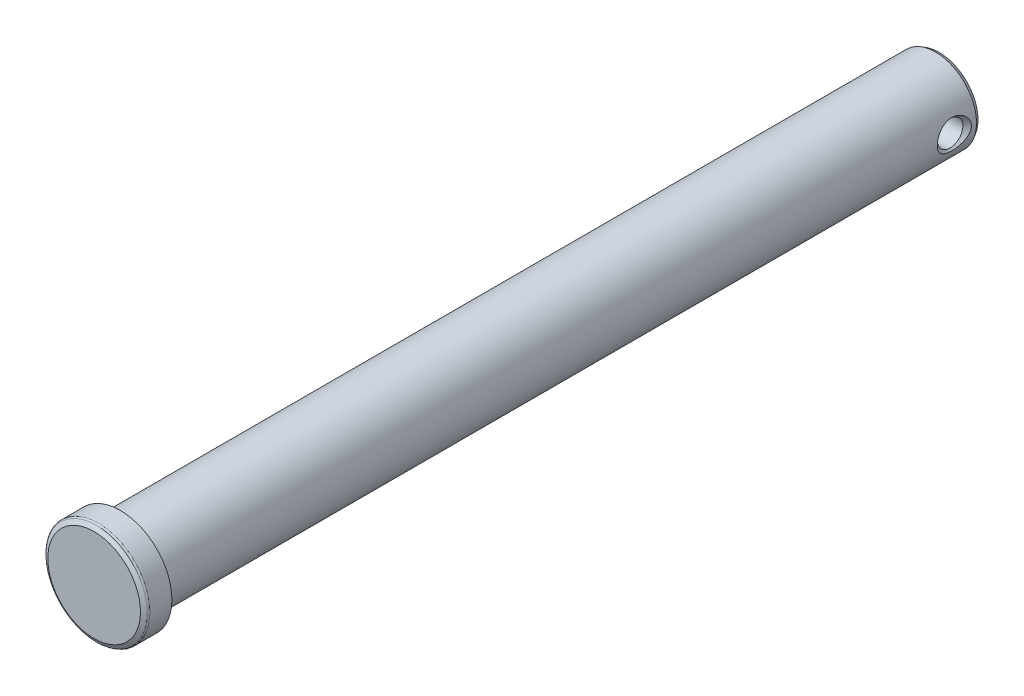
SolidWorks part; units mm, degrees
ref_plane "Front" through (0, 0, 0) normal (0, 0, 1) x (1, 0, 0)
ref_plane "Top" through (0, 0, 0) normal (0, 1, 0) x (1, 0, 0)
ref_plane "Right" through (0, 0, 0) normal (1, 0, 0) x (0, 0, -1)
sketch "Sketch1" plane through (0, 0, 0) normal (1, 0, 0) x (0, 0, -1)
  line L0 (-67.564, 0) -> (-63.5, 0) construction
  line L1 (-63.5, 0) -> (63.5, 0) construction
  line L2 (-67.564, 0) -> (-67.564, 7.1882)
  line L3 (-67.564, 7.1882) -> (-67.0947, 8.001)
  line L4 (-67.0947, 8.001) -> (-63.5, 8.001)
  line L5 (-63.5, 8.001) -> (-63.5, 6.35)
  line L6 (-63.5, 6.35) -> (62.9501, 6.35)
  line L7 (62.9501, 6.35) -> (63.5, 6.0325)
  line L8 (63.5, 6.0325) -> (63.5, 0)
  line L9 (-63.5, -6.35) -> (-63.5, -8.001)
  circle A0 centre (59.5122, 0) radius 1.9812
  point P4 (0, 0)
  point P17 (57.531, 0)
  dimension "Through Hole Diameter" = 3.9624
  dimension "Diameter" = 12.7
  dimension "D1" = 30
  dimension "D2" = 0.3175
  dimension "Head Height" = 4.064
  dimension "Head Diameter" = 16.002
  dimension "D5" = 0.8128
  dimension "Length" = 127
  dimension "Usable Length" = 121.031
sketch "Sketch2" plane through (0, 0, 0) normal (1, 0, 0) x (0, 0, -1)
  line L0 (63.5, 6.0325) -> (63.5, 0) construction
  line L1 (62.9501, 6.35) -> (63.5, 6.0325) construction
  line L2 (-63.5, 6.35) -> (62.9501, 6.35) construction
  line L3 (-63.5, 8.001) -> (-63.5, 6.35) construction
  line L4 (-67.0947, 8.001) -> (-63.5, 8.001) construction
  line L5 (-67.564, 7.1882) -> (-67.0947, 8.001) construction
  line L6 (-67.564, 0) -> (-67.564, 7.1882) construction
  line L7 (63.5, 6.0325) -> (63.5, 0)
  line L8 (62.9501, 6.35) -> (63.5, 6.0325)
  line L9 (-63.5, 6.35) -> (62.9501, 6.35)
  line L10 (-63.5, 8.001) -> (-63.5, 6.35)
  line L11 (-67.0947, 8.001) -> (-63.5, 8.001)
  line L12 (-67.564, 7.1882) -> (-67.0947, 8.001)
  line L13 (-67.564, 0) -> (-67.564, 7.1882)
  line L14 (-67.564, 0) -> (63.5, 0)
revolve "Revolve1" add sketch "Sketch2" angle 360 about L1
sketch "Sketch3" plane through (0, 0, 0) normal (1, 0, 0) x (0, 0, -1)
  circle A0 centre (59.5122, 0) radius 1.9812 construction
  circle A1 centre (59.5122, 0) radius 1.9812
extrude "Cut-Extrude1" cut sketch "Sketch3" against normal through all both and the other way through all
fillet "Fillet1" radius 0.3175 2 edges at (6.35, 0, 63.5) (8.001, 0, 67.0947)
sketch "Sketch4" plane through (0, 0, 0) normal (0, 1, 0) x (1, 0, 0)
  line L0 (6.35, 59.5122) -> (-6.35, 59.5122) construction
  line L1 (6.35, 59.5122) -> (6.35, 56.8706)
  line L2 (6.35, 56.8706) -> (3.7084, 59.5122)
  line L3 (6.35, -63.1825) -> (6.35, 57.531) construction
  line L4 (0, 59.5122) -> (0, 0) construction
  line L5 (-6.35, 56.8706) -> (-3.7084, 59.5122)
  line L6 (-6.35, 59.5122) -> (-6.35, 56.8706)
  line L7 (-6.35, 59.5122) -> (-3.7084, 59.5122)
  line L8 (3.7084, 59.5122) -> (6.35, 59.5122)
  dimension "D1" = 45
  dimension "D2" = 5.2832
revolve "Cut-Revolve1" cut sketch "Sketch4" angle 360 about L0
equation "\"D2@Sketch1\"=\"Diameter@Sketch1\" * .025"
equation "\"D5@Sketch1\" = \"Head Height@Sketch1\" * .2"
equation "\"D1@Fillet1\"=\"D2@Sketch1\""
equation "\"D2@Sketch4\"=\"Through Hole Diameter@Sketch1\" * 4/3"
